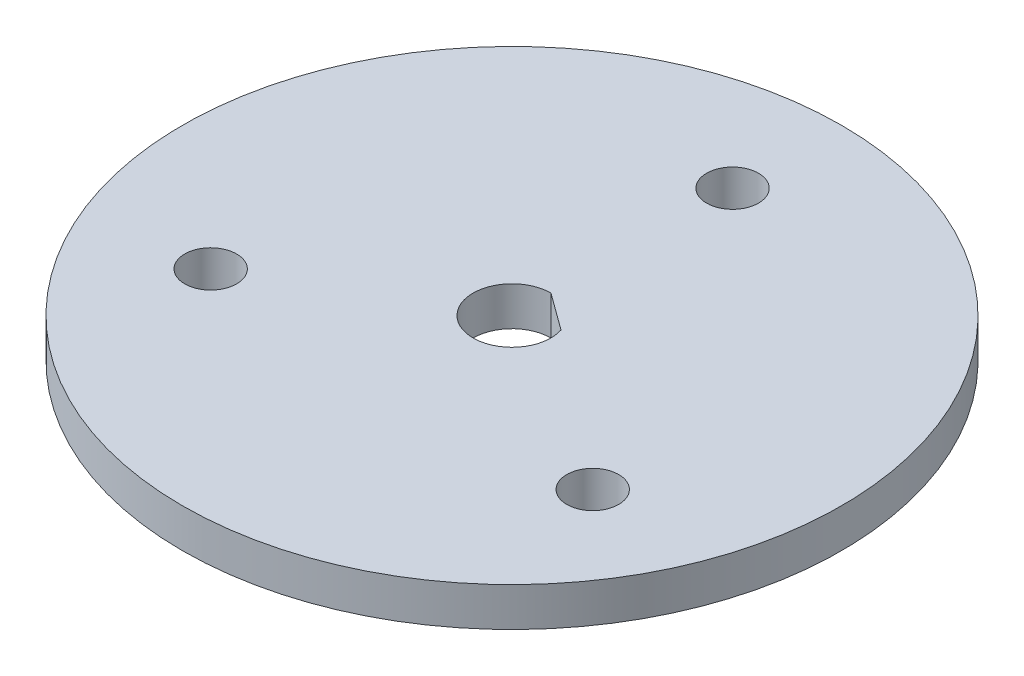
SolidWorks part; units mm, degrees
ref_plane "Front" through (0, 0, 0) normal (0, 0, 1) x (1, 0, 0)
ref_plane "Top" through (0, 0, 0) normal (0, 1, 0) x (1, 0, 0)
ref_plane "Right" through (0, 0, 0) normal (1, 0, 0) x (0, 0, -1)
sketch "Sketch1" plane through (0, 0, 0) normal (0, 1, 0) x (1, 0, 0)
  circle A0 centre (0, 0) radius 25.4
  dimension "D1" = 50.8
extrude "Boss-Extrude1" add sketch "Sketch1" along normal blind 3
sketch "Sketch2" plane through (0, 3, 0) normal (0, 1, 0) x (1, 0, 0)
  line L0 (0, 3) -> (2.8544, 0.9232)
  circle A0 centre (0, 0) radius 3
  circle A2 centre (0, 17) radius 2
  circle A3 centre (14.7224, -8.5) radius 2
  circle A4 centre (-14.7224, -8.5) radius 2
  point P14 (0, 0)
  dimension "D1" = 3.53
  dimension "D2" = 3
extrude "Cut-Extrude1" cut sketch "Sketch2" against normal blind 5 contours L0 A0
sketch "Sketch3" plane through (0, 3, 0) normal (0, 1, 0) x (1, 0, 0)
  circle A0 centre (0, 0) radius 17
  circle A1 centre (0, 17) radius 2
  circle A2 centre (14.7224, -8.5) radius 2
  circle A3 centre (-14.7224, -8.5) radius 2
  point P11 (0, 0)
  dimension "D1" = 3
extrude "Cut-Extrude2" cut sketch "Sketch3" against normal blind 5 contours A0 A1 | A0 A3 | A0 A3 | A0 A1 | A2
